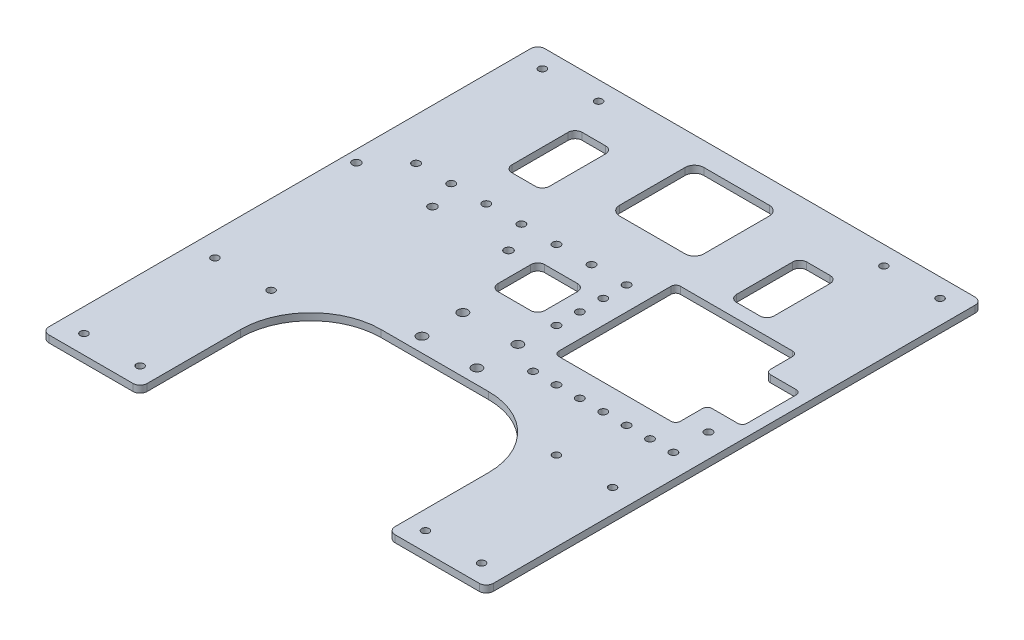
SolidWorks part; units mm, degrees
ref_plane "前视基准面" through (0, 0, 0) normal (0, 0, 1) x (1, 0, 0)
ref_plane "上视基准面" through (0, 0, 0) normal (0, 1, 0) x (1, 0, 0)
ref_plane "右视基准面" through (0, 0, 0) normal (1, 0, 0) x (0, 0, -1)
other "Configuration Table"
sketch "草图1" plane through (0, 0, 0) normal (0, 1, 0) x (1, 0, 0)
  line L1 (-95, 3) -> (-95, 209)
  line L2 (-92, 212) -> (92, 212)
  line L3 (95, 209) -> (95, 3)
  line L4 (-11.75, 79.25) -> (11.75, 79.25) construction
  line L5 (0, 212) -> (0, 204) construction
  line L6 (-56, 186) -> (-56, 162)
  line L7 (-53, 159) -> (-43, 159)
  line L8 (-40, 162) -> (-40, 186)
  line L9 (-43, 189) -> (-53, 189)
  line L10 (43, 189) -> (53, 189)
  line L11 (40, 162) -> (40, 186)
  line L12 (53, 159) -> (43, 159)
  line L13 (56, 186) -> (56, 162)
  line L17 (77, 139.5) -> (88, 139.5)
  line L21 (-14, 166) -> (14, 166)
  line L27 (-23, 73) -> (23, 73)
  line L29 (-92, 0) -> (-56, 0)
  line L30 (-53, 3) -> (-53, 43)
  line L31 (53, 43) -> (53, 3)
  line L32 (56, 0) -> (92, 0)
  line L33 (-18, 170) -> (-18, 198)
  line L34 (-14, 202) -> (14, 202)
  line L35 (18, 170) -> (18, 198)
  line L36 (-18, 166) -> (18, 202) construction
  line L37 (-18, 202) -> (18, 166) construction
  line L38 (25, 153) -> (73, 153)
  line L39 (23, 151) -> (23, 103)
  line L40 (25, 101) -> (73, 101)
  line L41 (75, 151) -> (75, 141.5)
  line L42 (90, 137.5) -> (90, 116.5)
  line L43 (88, 114.5) -> (77, 114.5)
  line L44 (75, 112.5) -> (75, 103)
  circle A0 centre (-11.75, 96.75) radius 2.1
  circle A1 centre (11.75, 96.75) radius 2.1
  circle A2 centre (11.75, 79.25) radius 2.1
  circle A3 centre (-11.75, 79.25) radius 2.1
  circle A4 centre (-85, 204) radius 1.6
  circle A5 centre (-61, 204) radius 1.6
  circle A6 centre (-61, 8) radius 1.6
  circle A7 centre (-85, 8) radius 1.6
  arc A8 (-56, 162) -> (-53, 159) centre (-53, 162) ccw
  arc A9 (-43, 159) -> (-40, 162) centre (-43, 162) ccw
  arc A10 (-40, 186) -> (-43, 189) centre (-43, 186) ccw
  arc A11 (-56, 186) -> (-53, 189) centre (-53, 186) cw
  arc A12 (56, 186) -> (53, 189) centre (53, 186) ccw
  arc A13 (40, 186) -> (43, 189) centre (43, 186) cw
  arc A14 (43, 159) -> (40, 162) centre (43, 162) cw
  arc A15 (56, 162) -> (53, 159) centre (53, 162) cw
  circle A16 centre (85, 8) radius 1.6
  circle A17 centre (61, 8) radius 1.6
  circle A18 centre (61, 204) radius 1.6
  circle A19 centre (85, 204) radius 1.6
  arc A20 (92, 212) -> (95, 209) centre (92, 209) cw
  arc A21 (-95, 209) -> (-92, 212) centre (-92, 209) cw
  arc A32 (53, 3) -> (56, 0) centre (56, 3) ccw
  arc A33 (-56, 0) -> (-53, 3) centre (-56, 3) ccw
  arc A34 (95, 3) -> (92, 0) centre (92, 3) cw
  arc A35 (-95, 3) -> (-92, 0) centre (-92, 3) ccw
  arc A36 (23, 73) -> (53, 43) centre (23, 43) cw
  arc A37 (-53, 43) -> (-23, 73) centre (-23, 43) cw
  arc A38 (14, 202) -> (18, 198) centre (14, 198) cw
  arc A39 (14, 166) -> (18, 170) centre (14, 170) ccw
  arc A40 (-14, 166) -> (-18, 170) centre (-14, 170) cw
  arc A41 (-18, 198) -> (-14, 202) centre (-14, 198) cw
  circle A42 centre (85, 64) radius 1.6
  circle A43 centre (61, 64) radius 1.6
  circle A44 centre (-85, 64) radius 1.6
  circle A45 centre (-61, 64) radius 1.6
  arc A46 (88, 139.5) -> (90, 137.5) centre (88, 137.5) cw
  arc A47 (90, 116.5) -> (88, 114.5) centre (88, 116.5) cw
  arc A48 (77, 114.5) -> (75, 112.5) centre (77, 112.5) ccw
  arc A49 (73, 101) -> (75, 103) centre (73, 103) ccw
  arc A50 (73, 153) -> (75, 151) centre (73, 151) cw
  arc A51 (77, 139.5) -> (75, 141.5) centre (77, 141.5) cw
  arc A52 (23, 103) -> (25, 101) centre (25, 103) ccw
  arc A53 (25, 153) -> (23, 151) centre (25, 151) ccw
  point P0 (0, 184)
  point P14 (0, 79.25)
  point P31 (-56, 159)
  point P34 (-40, 159)
  point P39 (-56, 189)
  point P62 (95, 212)
  point P67 (53, 0)
  point P72 (-53, 0)
  point P77 (95, 0)
  point P81 (-95, 0)
  point P84 (53, 73)
  point P87 (-53, 73)
  point P90 (0, 73)
  point P120 (90, 127)
  point P121 (23, 127)
  point P124 (90, 139.5)
  point P127 (90, 114.5)
  point P130 (75, 114.5)
  point P133 (75, 101)
  point P136 (75, 153)
  point P139 (75, 139.5)
  dimension "D1" = 4.2
  dimension "D4" = 17.5
  dimension "D9" = 3.2
  dimension "D16" = 3
  dimension "D17" = 3
  dimension "D18" = 3
  dimension "D20" = 139
  dimension "D23" = 4
  dimension "D30" = 15
  dimension "D3" = 106
  dimension "D19" = 30
  dimension "D6" = 8
  dimension "D32" = 2
  dimension "D2" = 23.5
  dimension "D5" = 190
  dimension "D7" = 24
  dimension "D8" = 6.25
  dimension "D10" = 8
  dimension "D11" = 61
  dimension "D12" = 16
  dimension "D13" = 30
  dimension "D14" = 40
  dimension "D15" = 15
  dimension "D21" = 10
  dimension "D22" = 36
  dimension "D24" = 212
  dimension "D25" = 56
  dimension "D26" = 106
  dimension "D27" = 52
  dimension "D28" = 20
  dimension "D29" = 59
  dimension "36" = 36
  dimension "D31" = 25
extrude "凸台-拉伸1" add sketch "草图1" along normal blind 3
sketch "草图2" plane through (0, 0, 0) normal (0, -1, 0) x (1, 0, 0)
  line L0 (92, -212) -> (-92, -212) construction
  line L1 (-95, -209) -> (-95, -3) construction
  line L2 (-90, -129.5) -> (-25, -129.5)
  point P0 (-90, -129.5)
  point P5 (-57.5, -129.5)
  dimension "D1" = 82.5
  dimension "D2" = 5
  dimension "D3" = 65
sketch "草图3" plane through (0, 0, 0) normal (0, -1, 0) x (-1, 0, 0)
  point P0 (90, 129.5)
  point P3 (57.5, 129.5)
  point P6 (25, 129.5)
hole_wizard "孔1" positions "草图3" profile "草图4" legacy end condition through all
sketch "草图4" plane through (-90, 0, -129.5) normal (1, 0, 0) x (0, 0, -1)
  line L0 (0, 0) -> (0, 3)
  line L1 (0, 3) -> (1.75, 3)
  line L2 (1.75, 3) -> (1.75, 0)
  line L3 (1.75, 0) -> (0, 0)
  line L4 (0, 110) -> (0, -10) construction
  dimension "直径" = 3.5
  dimension "深度" = 3
sketch "草图5" plane through (0, 3, 0) normal (0, 1, 0) x (1, 0, 0)
  line L0 (23, 142) -> (-95, 142)
  line L1 (23, 151) -> (23, 103) construction
  line L2 (-95, 209) -> (-95, 3) construction
  line L3 (92, 212) -> (-92, 212) construction
  point P8 (13, 142)
  dimension "D1" = 70
  dimension "D2" = 10
sketch "草图6" plane through (0, 3, 0) normal (0, 1, 0) x (1, 0, 0)
  point P0 (13, 142)
hole_wizard "孔2" positions "草图6" profile "草图7" legacy end condition up to next
sketch "草图7" plane through (13, 3, -142) normal (1, 0, 0) x (0, 0, 1)
  line L0 (0, 0) -> (0, 3)
  line L1 (0, 3) -> (1.65, 3)
  line L2 (1.65, 3) -> (1.65, 0)
  line L3 (1.65, 0) -> (0, 0)
  line L4 (0, 110) -> (0, -10) construction
  dimension "直径" = 3.3
  dimension "深度" = 3
pattern_linear "阵列(线性)1" count 7 spacing 15 along (-1, 0, 0) of "孔2"
pattern_linear "阵列(线性)2" count 4 spacing 10 along (0, 0, 1) of "孔2"
sketch "草图8" plane through (0, 3, 0) normal (0, 1, 0) x (1, 0, 0)
  line L0 (95, 90) -> (25, 90)
  line L1 (95, 3) -> (95, 209) construction
  line L2 (56, 0) -> (92, 0) construction
  dimension "D1" = 70
  dimension "D2" = 90
sketch "草图9" plane through (0, 3, 0) normal (0, 1, 0) x (1, 0, 0)
  point P0 (25, 90)
hole_wizard "孔3" positions "草图9" profile "草图10" legacy end condition up to next
sketch "草图10" plane through (25, 3, -90) normal (1, 0, 0) x (0, 0, 1)
  line L0 (0, 0) -> (0, 3)
  line L1 (0, 3) -> (1.65, 3)
  line L2 (1.65, 3) -> (1.65, 0)
  line L3 (1.65, 0) -> (0, 0)
  line L4 (0, 110) -> (0, -10) construction
  dimension "直径" = 3.3
  dimension "深度" = 3
pattern_linear "阵列(线性)3" count 7 spacing 10 along (1, 0, 0) of "孔3"
sketch "草图11" plane through (0, 3, 0) normal (0, 1, 0) x (1, 0, 0)
  line L0 (85, 90) -> (85, 105)
  dimension "D1" = 15
sketch "草图12" plane through (0, 3, 0) normal (0, 1, 0) x (1, 0, 0)
  point P0 (85, 105)
hole_wizard "孔4" positions "草图12" profile "草图13" legacy end condition up to next
sketch "草图13" plane through (85, 3, -105) normal (1, 0, 0) x (0, 0, 1)
  line L0 (0, 0) -> (0, 3)
  line L1 (0, 3) -> (1.65, 3)
  line L2 (1.65, 3) -> (1.65, 0)
  line L3 (1.65, 0) -> (0, 0)
  line L4 (0, 110) -> (0, -10) construction
  dimension "直径" = 3.3
  dimension "深度" = 3
sketch "草图14" plane through (0, 3, 0) normal (0, 1, 0) x (1, 0, 0)
  line L0 (-95, 209) -> (-95, 3) construction
  line L1 (-15, 132) -> (5, 132)
  line L2 (-15, 132) -> (-15, 112)
  line L3 (-15, 112) -> (5, 112)
  line L4 (5, 132) -> (5, 112)
  line L5 (92, 212) -> (-92, 212) construction
  dimension "D1" = 80
  dimension "D2" = 80
  dimension "D3" = 20
  dimension "D4" = 20
extrude "切除-拉伸1" cut sketch "草图14" against normal blind 10
sketch "草图15" plane through (0, 3, 0) normal (0, 1, 0) x (1, 0, 0)
  line L0 (5, 132) -> (-15, 132) construction
  line L1 (-15, 112) -> (5, 112) construction
  line L2 (-15, 132) -> (-15, 112) construction
  line L3 (5, 112) -> (5, 132) construction
  point P0 (-13.5, 132)
  point P1 (3.5, 132)
  point P4 (-13.5, 112)
  point P5 (3.5, 112)
  dimension "D1" = 1.5
  dimension "D2" = 1.5
  dimension "D3" = 1.5
  dimension "D4" = 1.5
fillet "圆角1" radius 3 4 edges at (-15, 1.5, -112) (5, 1.5, -112) (5, 1.5, -132) (-15, 1.5, -132)
